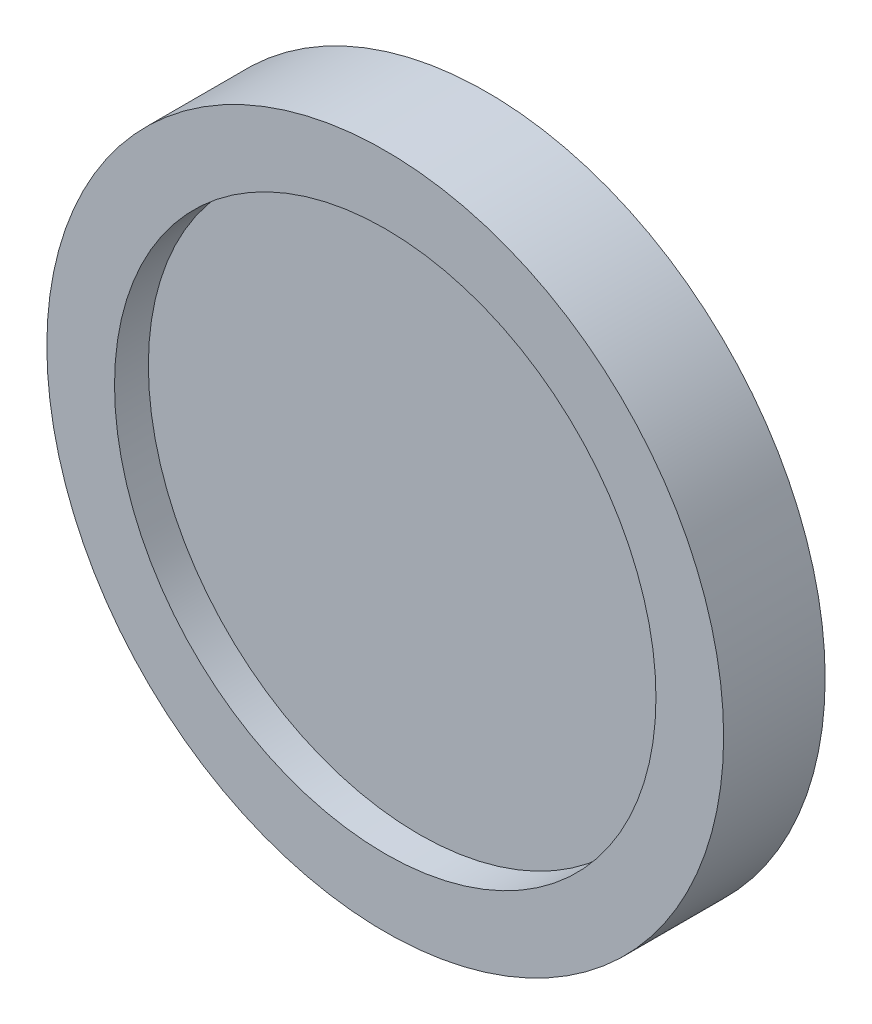
SolidWorks part; units mm, degrees
ref_plane "Front Plane" through (0, 0, 0) normal (0, 0, 1) x (1, 0, 0)
ref_plane "Top Plane" through (0, 0, 0) normal (0, 1, 0) x (1, 0, 0)
ref_plane "Right Plane" through (0, 0, 0) normal (1, 0, 0) x (0, 0, -1)
sketch "草图1" plane through (0, 0, 0) normal (0, 0, 1) x (1, 0, 0)
  circle A0 centre (0, 0) radius 50
  dimension "D1" = 100
extrude "凸台-拉伸1" add sketch "草图1" along normal blind 15
sketch "草图2" plane through (0, 0, 15) normal (0, 0, 1) x (1, 0, 0)
  point P0 (0, 0)
shell "抽壳1" thickness 10
